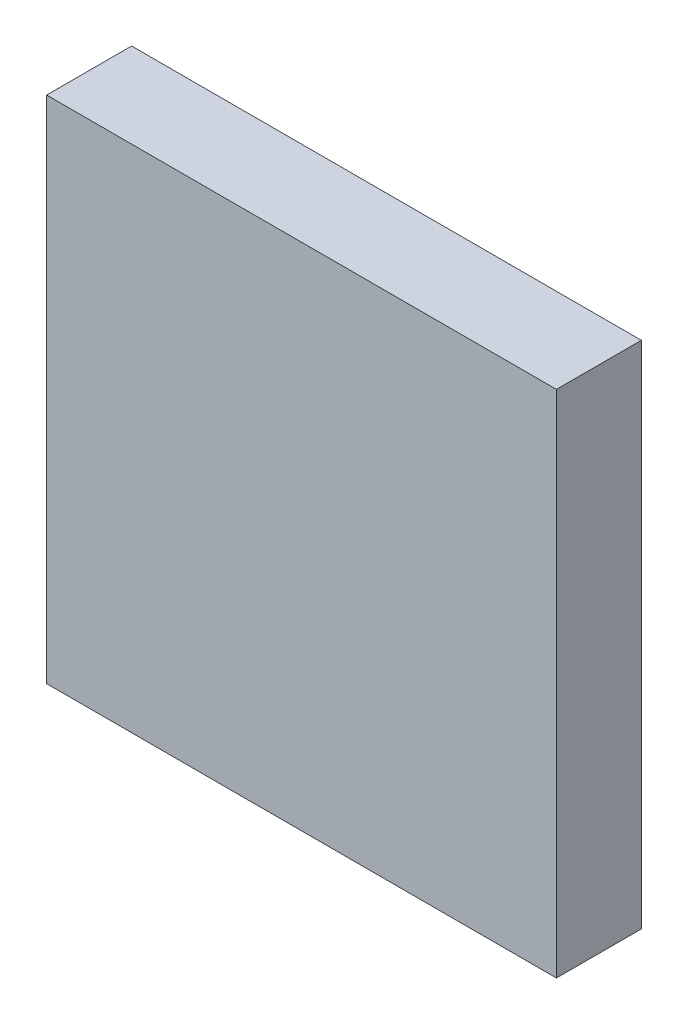
SolidWorks part; units mm, degrees
ref_plane "Plan de face" through (0, 0, 0) normal (0, 0, 1) x (1, 0, 0)
ref_plane "Plan de dessus" through (0, 0, 0) normal (0, 1, 0) x (1, 0, 0)
ref_plane "Plan de droite" through (0, 0, 0) normal (1, 0, 0) x (0, 0, -1)
sketch "Esquisse1" plane through (0, 0, 0) normal (0, 0, 1) x (1, 0, 0)
  line L1 (-6, 6) -> (6, 6)
  line L2 (-6, 6) -> (-6, -6)
  line L3 (-6, -6) -> (6, -6)
  line L4 (6, 6) -> (6, -6)
  dimension "D1" = 12
  dimension "D2" = 12
  dimension "D3" = 6
  dimension "D4" = 6
extrude "Boss.-Extru.1" add sketch "Esquisse1" along normal blind 2
sketch "Esquisse2" plane through (0, 0, 0) normal (0, 0, -1) x (-1, 0, 0)
  line L1 (-2, 2) -> (2, 2)
  line L2 (-2, 2) -> (-2, -2)
  line L3 (-2, -2) -> (2, -2)
  line L4 (2, 2) -> (2, -2)
  dimension "D1" = 4
  dimension "D2" = 4
  dimension "D3" = 2
  dimension "D4" = 2
extrude "Boss.-Extru.2" add sketch "Esquisse2" along normal blind 4
